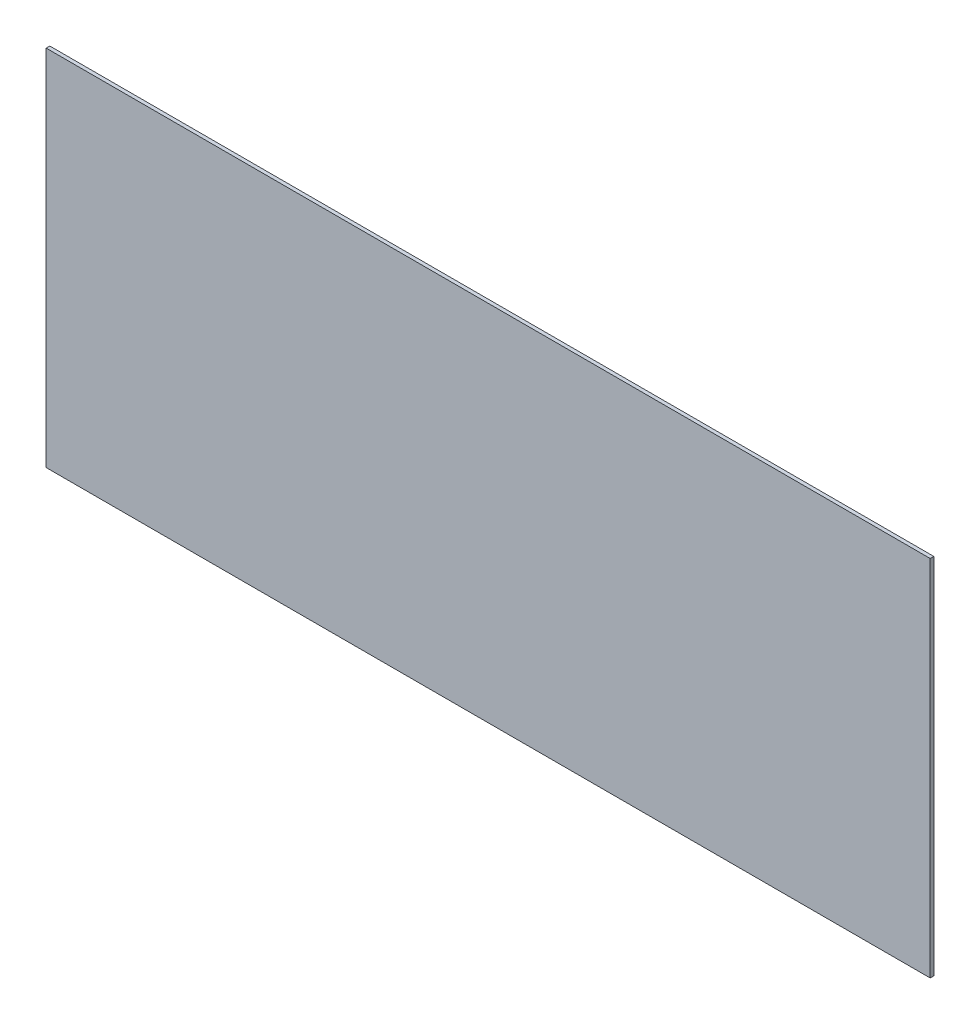
SolidWorks part; units mm, degrees
ref_plane "Front Plane" through (0, 0, 0) normal (0, 0, 1) x (1, 0, 0)
ref_plane "Top Plane" through (0, 0, 0) normal (0, 1, 0) x (1, 0, 0)
ref_plane "Right Plane" through (0, 0, 0) normal (1, 0, 0) x (0, 0, -1)
sketch "Sketch1" plane through (0, 0, 0) normal (0, 0, 1) x (1, 0, 0)
  line L0 (0, 0) -> (730, 0)
  line L1 (0, 0) -> (0, 300)
  line L2 (0, 300) -> (730, 300)
  line L3 (730, 300) -> (730, 0)
  dimension "D1" = 300
  dimension "D2" = 730
extrude "Boss-Extrude1" add sketch "Sketch1" along normal blind 3 contours L2 L3 L0 L1
